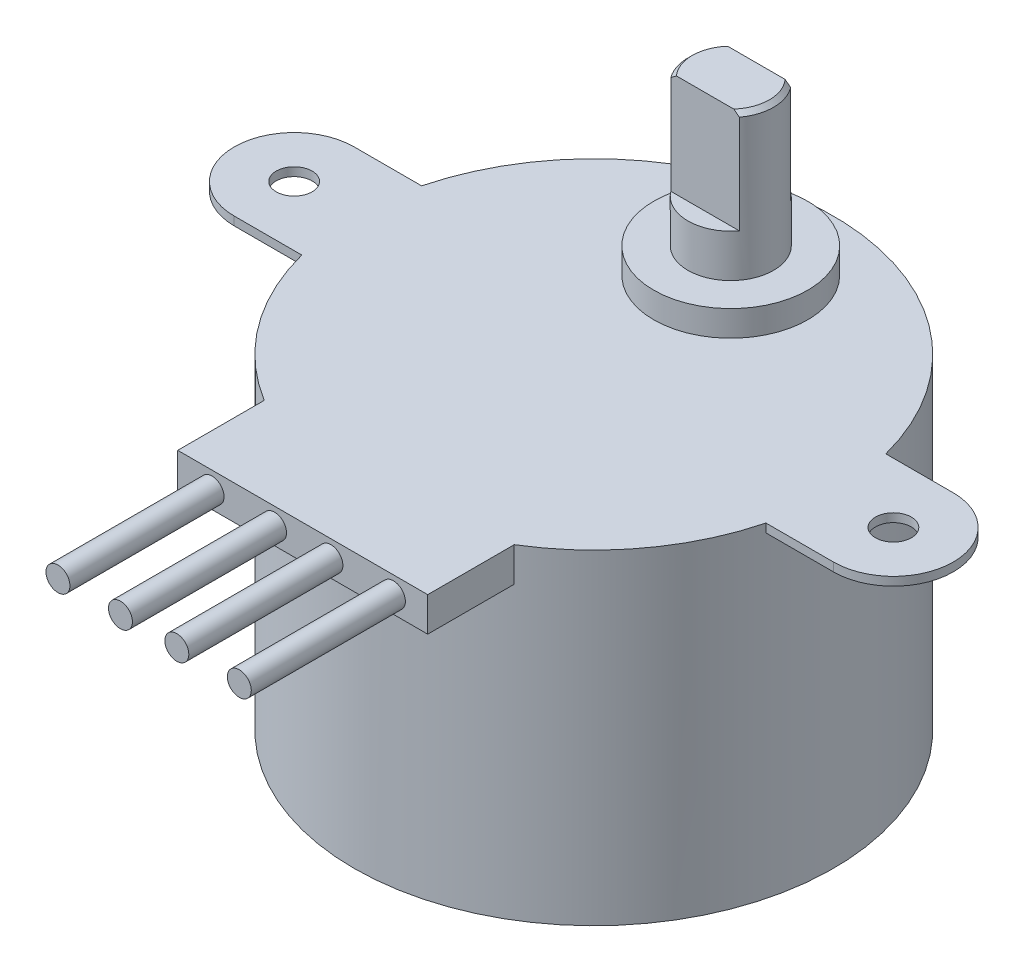
SolidWorks part; units mm, degrees
ref_plane "Front Plane" through (0, 0, 0) normal (0, 0, 1) x (1, 0, 0)
ref_plane "Top Plane" through (0, 0, 0) normal (0, 1, 0) x (1, 0, 0)
ref_plane "Right Plane" through (0, 0, 0) normal (1, 0, 0) x (0, 0, -1)
sketch "Sketch1" plane through (0, 0, 0) normal (0, 1, 0) x (1, 0, 0)
  circle A0 centre (0, 0) radius 14
  point P3 (0, 0)
  dimension "D1" = 28
extrude "Boss-Extrude1" add sketch "Sketch1" along normal blind 19
sketch "Sketch2" plane through (0, 19, 0) normal (0, 1, 0) x (1, 0, 0)
  line L0 (0, 0) -> (0, 8)
  circle A0 centre (0, 8) radius 4.5
  dimension "D1" = 8
extrude "Boss-Extrude2" add sketch "Sketch2" along normal blind 1.5 contours A0
sketch "Sketch3" plane through (0, 20.5, 0) normal (0, 1, 0) x (1, 0, 0)
  circle A0 centre (0, 8) radius 2.5
extrude "Boss-Extrude3" add sketch "Sketch3" along normal blind 2.5
sketch "Sketch4" plane through (0, 23, 0) normal (0, 1, 0) x (1, 0, 0)
  circle A0 centre (0, 8) radius 2.5
  dimension "D1" = 5
extrude "Boss-Extrude4" add sketch "Sketch4" along normal blind 6
chamfer "Chamfer1" distance 0.25 1 edges at (0, 29, -5.5)
sketch "Sketch6" plane through (0, 19, 0) normal (0, 1, 0) x (1, 0, 0)
  line L0 (0, 0) -> (0, 3.5) construction
  line L1 (0, 0) -> (14, 0) construction
  line L2 (-17.5, 3.5) -> (17.5, 3.5)
  line L3 (17.5, -3.5) -> (-17.5, -3.5)
  line L4 (14, 0) -> (16.45, 0) construction
  line L5 (16.45, 0) -> (17.5, 0)
  circle A0 centre (17.5, 0) radius 1.05
  arc A1 (17.5, -3.5) -> (17.5, 3.5) centre (17.5, 0) ccw
  arc A2 (17.5, 3.5) -> (14, 0) centre (17.5, 0) ccw construction
  arc A3 (14, 0) -> (17.5, -3.5) centre (17.5, 0) ccw construction
  circle A4 centre (-17.5, 0) radius 1.05
  arc A5 (-17.5, -3.5) -> (-17.5, 3.5) centre (-17.5, 0) cw
  point P13 (0, -3.5)
  circle M9 centre (0, 0) radius 14
  dimension "D3" = 2.1
  dimension "D1" = 3.5
  dimension "D2" = 17.5
extrude "Boss-Extrude5" add sketch "Sketch6" against normal blind 0.5 contours A5 L3 L2 A4 M9 | L3 A1 L2 A0 M9
sketch "Sketch7" plane through (0, 29, 0) normal (0, 1, 0) x (1, 0, 0)
  line L0 (0, 8) -> (0, 9.5) construction
  line L1 (0, 8) -> (0, 6.5) construction
  line L2 (0, 9.5) -> (-3.8527, 9.5)
  line L3 (-3.8527, 9.5) -> (-3.8527, 12.8083)
  line L4 (-3.8527, 12.8083) -> (3.6924, 12.8083)
  line L5 (3.6924, 12.8083) -> (3.6924, 9.5)
  line L6 (3.6924, 9.5) -> (0, 9.5)
  line L7 (0, 8) -> (3.0228, 8) construction
  line L8 (3.6924, 6.5) -> (0, 6.5)
  line L9 (3.6924, 3.1917) -> (3.6924, 6.5)
  line L10 (-3.8527, 3.1917) -> (3.6924, 3.1917)
  line L11 (-3.8527, 6.5) -> (-3.8527, 3.1917)
  line L12 (0, 6.5) -> (-3.8527, 6.5)
  dimension "D1" = 1.5
extrude "Cut-Extrude1" cut sketch "Sketch7" against normal blind 6
sketch "Sketch8" plane through (0, 19, 0) normal (0, 1, 0) x (1, 0, 0)
  line L0 (7.3, -17) -> (-7.3, -17)
  line L1 (7.3, 0) -> (7.3, -17)
  line L2 (-7.3, 0) -> (7.3, 0)
  line L3 (0, 0) -> (0, -7.0426) construction
  line L4 (-7.3, 0) -> (-7.3, -17)
  point P7 (0, -17)
  dimension "D1" = 17
  dimension "D2" = 7.3
extrude "Boss-Extrude6" add sketch "Sketch8" against normal blind 2
sketch "Sketch9" plane through (0, 0, 17) normal (0, 0, 1) x (1, 0, 0)
  line L0 (0, 19) -> (0, 17)
  line L1 (-7.3, 19) -> (7.3, 19) construction
  line L2 (-7.3, 17) -> (7.3, 17) construction
  line L6 (-3.2917, 19) -> (-7.3, 17) construction
  line L7 (-3.2917, 19) -> (0, 17) construction
  circle A2 centre (-5.2958, 18) radius 0.7
  circle A3 centre (-1.6458, 18) radius 0.7
  circle A4 centre (1.6458, 18) radius 0.7
  circle A5 centre (5.2958, 18) radius 0.7
extrude "Boss-Extrude7" add sketch "Sketch9" along normal blind 9 contours A3 | A4 | A5 | A2
